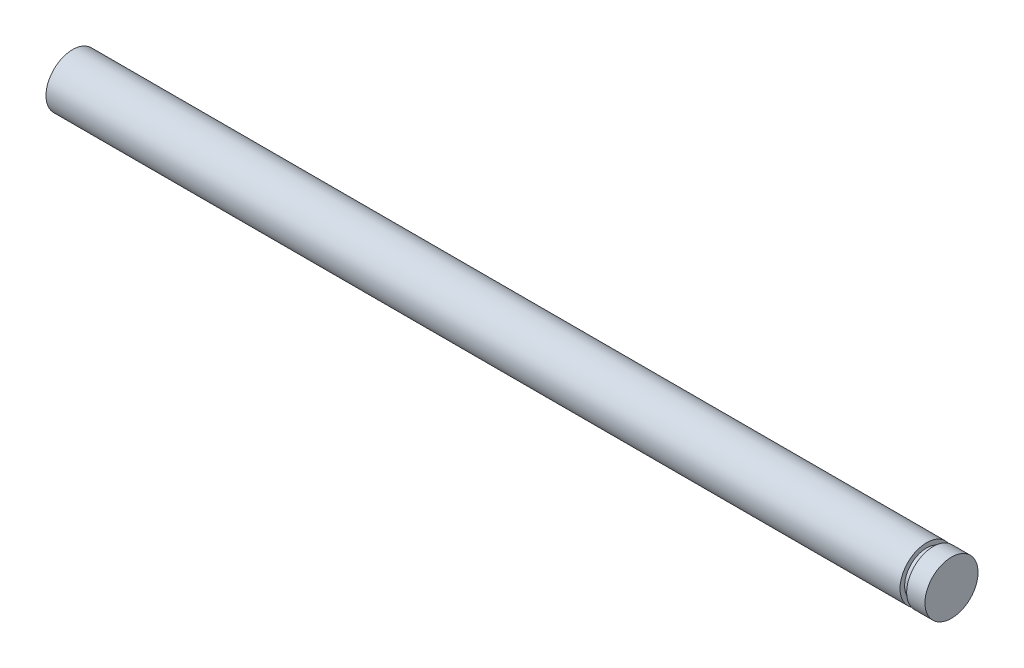
SolidWorks part; units mm, degrees
ref_plane "Front Plane" through (0, 0, 0) normal (0, 0, 1) x (1, 0, 0)
ref_plane "Top Plane" through (0, 0, 0) normal (0, 1, 0) x (1, 0, 0)
ref_plane "Right Plane" through (0, 0, 0) normal (1, 0, 0) x (0, 0, -1)
sketch "Sketch1" plane through (0, 0, 0) normal (0, 0, 1) x (1, 0, 0)
  line L0 (0, 0) -> (0, 267897.7273) construction
  line L1 (0, 0) -> (267897.7273, 0) construction
  line L2 (0, 0) -> (609.6, 0)
  line L3 (609.6, 0) -> (609.6, -18.415)
  line L4 (609.6, -18.415) -> (596.9, -18.415)
  line L5 (596.9, -18.415) -> (596.9, -15.24)
  line L6 (596.9, -15.24) -> (592.328, -15.24)
  line L7 (592.328, -15.24) -> (592.328, -18.415)
  line L8 (592.328, -18.415) -> (0, -18.415)
  line L9 (0, 0) -> (0, -18.415)
  dimension "D1" = 609.6
  dimension "D2" = 18.415
  dimension "D3" = 15.24
  dimension "D4" = 12.7
  dimension "D5" = 4.572
revolve "Revolve1" add sketch "Sketch1" angle 360 about L2
